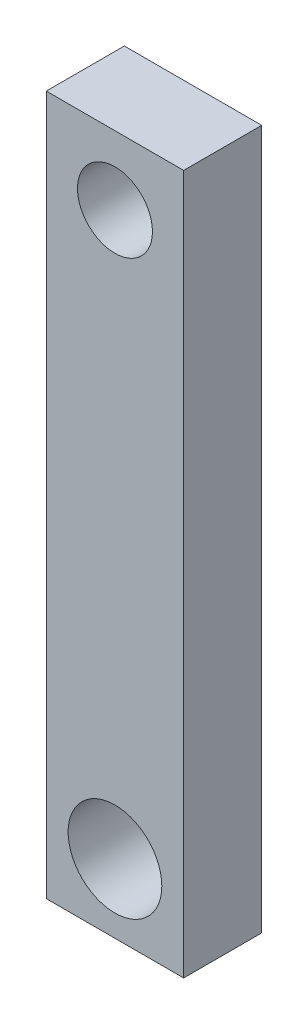
SolidWorks part; units mm, degrees
ref_plane "Front Plane" through (0, 0, 0) normal (0, 0, 1) x (1, 0, 0)
ref_plane "Top Plane" through (0, 0, 0) normal (0, 1, 0) x (1, 0, 0)
ref_plane "Right Plane" through (0, 0, 0) normal (1, 0, 0) x (0, 0, -1)
sketch "Sketch1" plane through (0, 0, 0) normal (0, 0, 1) x (1, 0, 0)
  line L1 (-22, -22) -> (22, -22)
  line L2 (-22, -22) -> (-22, 202)
  line L3 (-22, 202) -> (22, 202)
  line L4 (22, -22) -> (22, 202)
  circle A0 centre (0, 0) radius 15
  circle A1 centre (0, 180) radius 12
extrude "Boss-Extrude1" add sketch "Sketch1" along normal blind 25
